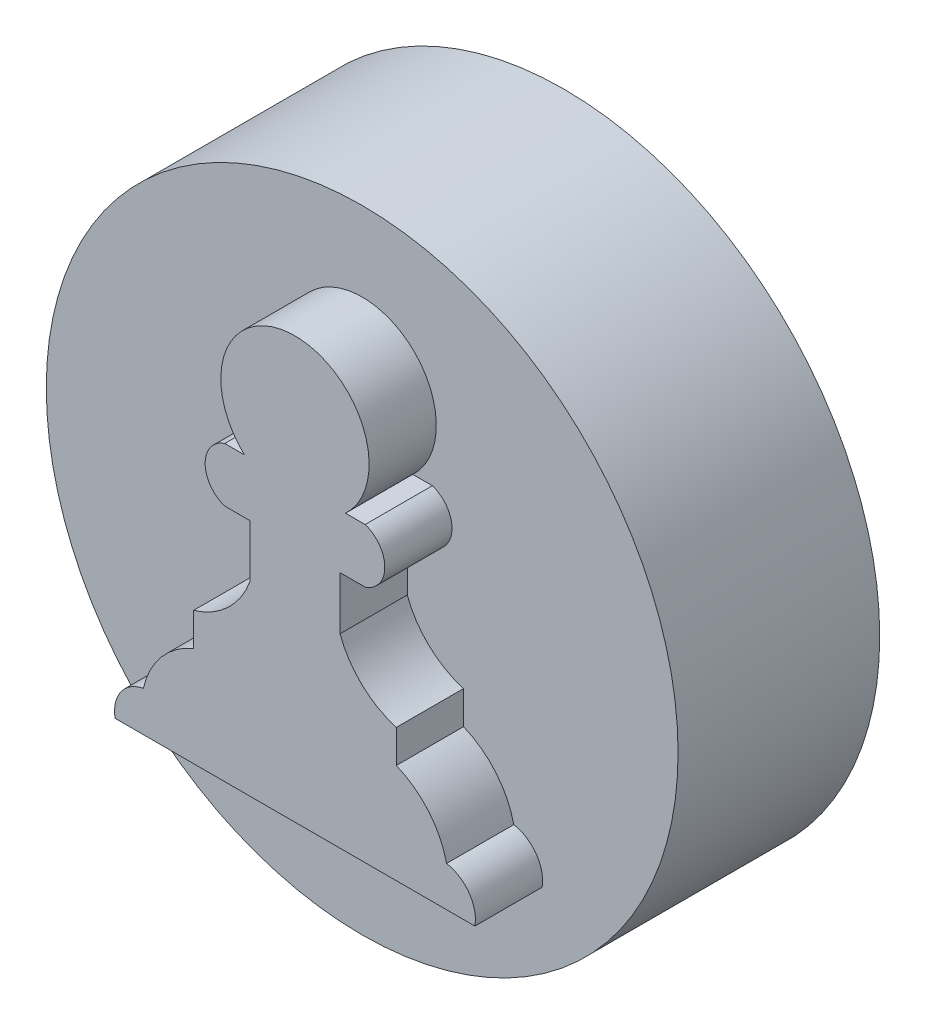
SolidWorks part; units mm, degrees
ref_plane "Front Plane" through (0, 0, 0) normal (0, 0, 1) x (1, 0, 0)
ref_plane "Top Plane" through (0, 0, 0) normal (0, 1, 0) x (1, 0, 0)
ref_plane "Right Plane" through (0, 0, 0) normal (1, 0, 0) x (0, 0, -1)
sketch "Sketch1" plane through (0, 0, 0) normal (0, 0, 1) x (1, 0, 0)
  circle A0 centre (0, 0) radius 8.763
  circle A1 centre (0, 0) radius 11.938
  dimension "D1" = 17.526
  dimension "D2" = 23.876
extrude "Boss-Extrude1" add sketch "Sketch1" along normal blind 5.08
sketch "Sketch2" plane through (0, 0, 5.08) normal (0, 0, 1) x (1, 0, 0)
  circle A0 centre (0, 0) radius 11.938
extrude "Boss-Extrude2" add sketch "Sketch2" along normal blind 2.54
sketch "Sketch3" plane through (0, 0, 7.62) normal (0, 0, 1) x (1, 0, 0)
  line L0 (76.4074, 247.7537) -> (417.7408, 247.7537) construction
  line L1 (0, 0) -> (0, 10.7108) construction
  line L2 (6.7992, -6.9765) -> (-6.7992, -6.9765)
  line L5 (-6.7992, -6.9765) -> (-6.7992, -6.5324)
  line L11 (-3.8301, -3.2058) -> (-3.8301, -1.9587)
  line L15 (-1.7038, 2.0423) -> (-1.7038, 0.0418)
  line L22 (-1.9108, 4.0912) -> (-2.6528, 4.0912)
  line L23 (-1.7038, 2.0423) -> (-2.6528, 2.0423)
  line L26 (3.8301, -3.2058) -> (3.8301, -1.9587)
  line L27 (1.7038, 2.0423) -> (1.7038, 0.0418)
  line L28 (1.7038, 2.0423) -> (2.6528, 2.0423)
  line L29 (1.9108, 4.0912) -> (2.6528, 4.0912)
  arc A0 (1.9108, 4.0912) -> (-1.9108, 4.0912) centre (0, 6.1402) ccw
  arc A1 (-3.8301, -1.9587) -> (-1.7038, 0.0418) centre (-4.7519, 1.1513) ccw
  arc A2 (-5.729, -5.4623) -> (-3.8301, -3.2058) centre (-2.6127, -6.1575) cw
  arc A3 (-5.729, -5.4623) -> (-6.7992, -6.9765) centre (-5.507, -6.7545) ccw
  arc A4 (-2.6528, 4.0912) -> (-2.6528, 2.0423) centre (-2.3166, 3.0667) ccw
  arc A6 (5.729, -5.4623) -> (6.7992, -6.9765) centre (5.507, -6.7545) cw
  arc A7 (5.729, -5.4623) -> (3.8301, -3.2058) centre (2.6127, -6.1575) ccw
  arc A8 (3.8301, -1.9587) -> (1.7038, 0.0418) centre (4.7519, 1.1513) cw
  arc A9 (2.6528, 4.0912) -> (2.6528, 2.0423) centre (2.3166, 3.0667) cw
  point P4 (0, 0)
  point P15 (0, 10.7108)
  point P38 (0, 0)
extrude "Boss-Extrude3" add sketch "Sketch3" along normal blind 2.54 contours A3 A2 L11 A1 L15 L23 A4 L22 A0 L29 A9 L28 L27 A8 L26 A7 A6 L2
